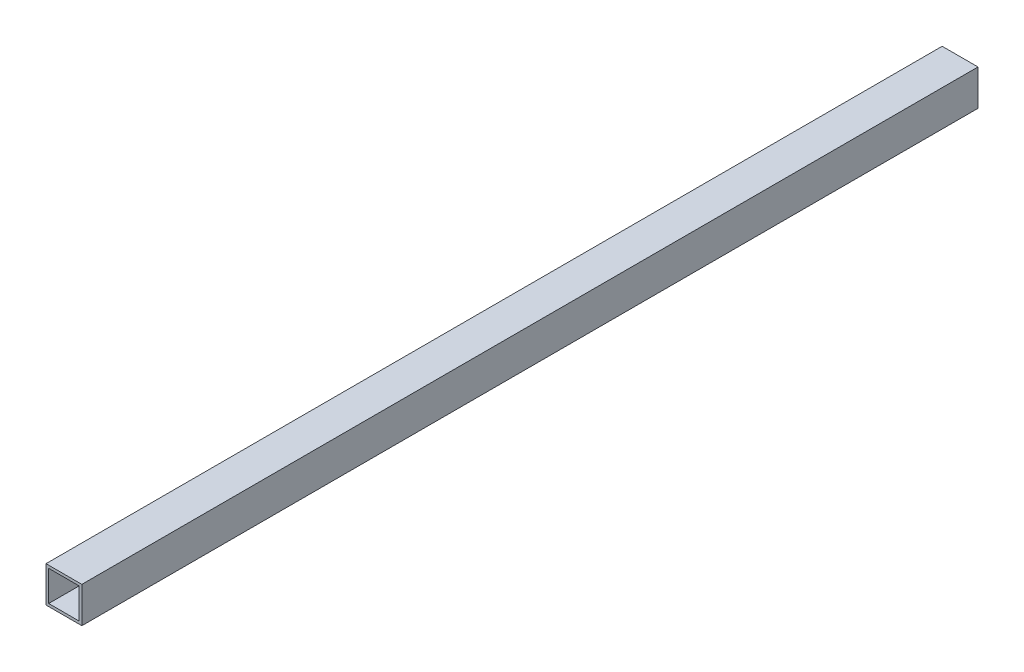
SolidWorks part; units mm, degrees
ref_plane "Front Plane" through (0, 0, 0) normal (0, 0, 1) x (1, 0, 0)
ref_plane "Top Plane" through (0, 0, 0) normal (0, 1, 0) x (1, 0, 0)
ref_plane "Right Plane" through (0, 0, 0) normal (1, 0, 0) x (0, 0, -1)
sketch "Sketch1" plane through (0, 0, 0) normal (0, 0, 1) x (1, 0, 0)
  line L1 (-20, 20) -> (20, 20)
  line L2 (-20, 20) -> (-20, -20)
  line L3 (-20, -20) -> (20, -20)
  line L4 (20, 20) -> (20, -20)
  line L5 (-20, 20) -> (20, -20) construction
  line L6 (-20, -20) -> (20, 20) construction
  point P0 (0, 0)
  dimension "D1" = 40
  dimension "D2" = 40
extrude "Boss-Extrude1" add sketch "Sketch1" along normal blind 1000
sketch "Sketch2" plane through (0, 0, 0) normal (0, 0, -1) x (-1, 0, 0)
  line L1 (-17, 17) -> (17, 17)
  line L2 (-17, 17) -> (-17, -17)
  line L3 (-17, -17) -> (17, -17)
  line L4 (17, 17) -> (17, -17)
  line L5 (-17, 17) -> (17, -17) construction
  line L6 (-17, -17) -> (17, 17) construction
  point P0 (0, 0)
  dimension "D1" = 34
  dimension "D2" = 34
extrude "Cut-Extrude1" cut sketch "Sketch2" against normal blind 1000
